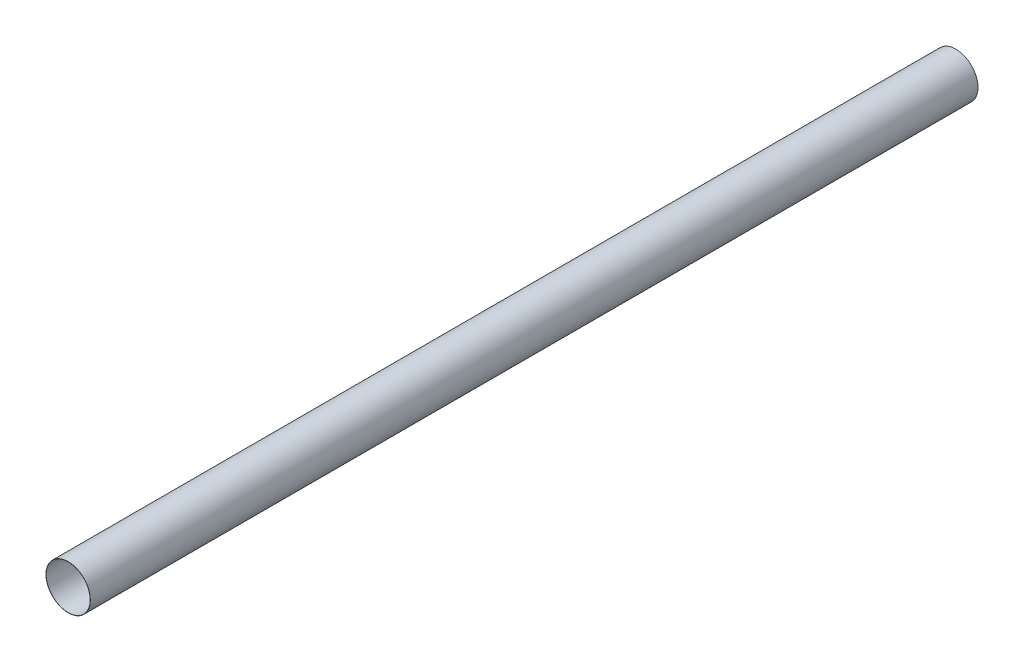
SolidWorks part; units mm, degrees
ref_plane "Front Plane" through (0, 0, 0) normal (0, 0, 1) x (1, 0, 0)
ref_plane "Top Plane" through (0, 0, 0) normal (0, 1, 0) x (1, 0, 0)
ref_plane "Right Plane" through (0, 0, 0) normal (1, 0, 0) x (0, 0, -1)
sketch "Sketch1" plane through (0, 0, 0) normal (0, 0, 1) x (1, 0, 0)
  circle A0 centre (0, 0) radius 250
  circle A1 centre (0, 0) radius 248
extrude "Boss-Extrude1" add sketch "Sketch1" along normal blind 10000
